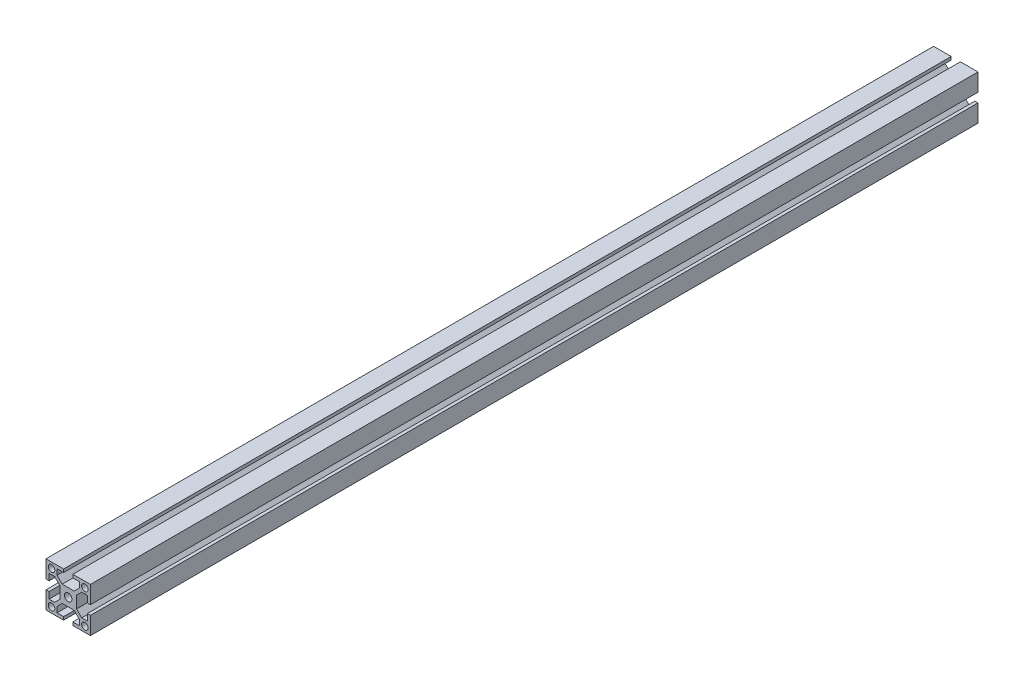
SolidWorks part; units mm, degrees
ref_plane "前视基准面" through (0, 0, 0) normal (0, 0, 1) x (1, 0, 0)
ref_plane "上视基准面" through (0, 0, 0) normal (0, 1, 0) x (1, 0, 0)
ref_plane "右视基准面" through (0, 0, 0) normal (1, 0, 0) x (0, 0, -1)
sketch "草图1" plane through (0, 0, 0) normal (0, 0, 1) x (1, 0, 0)
  line L0 (-0.0108, -0.0108) -> (37.1473, 37.1473) construction
  line L1 (-5.3895, -7.5108) -> (5.3678, -7.5108)
  line L2 (-7.5108, -5.3895) -> (-7.5108, 5.3678)
  line L3 (-5.3895, 7.4892) -> (5.3678, 7.4892)
  line L4 (7.4892, -5.3895) -> (7.4892, 5.3678)
  line L5 (-7.5108, -7.5108) -> (7.4892, 7.4892) construction
  line L6 (-7.5108, 7.4892) -> (7.4892, -7.5108) construction
  line L7 (7.4892, 5.3678) -> (12.1605, 10.0392)
  line L8 (19.9892, 19.9892) -> (19.9892, 4.1392)
  line L9 (19.9892, 19.9892) -> (4.1392, 19.9892)
  line L10 (19.9892, 4.1392) -> (17.1892, 4.1392)
  line L11 (4.1392, 19.9892) -> (4.1392, 17.1892)
  line L12 (17.1892, 4.1392) -> (17.1892, 10.0392)
  line L13 (12.1605, 10.0392) -> (17.1892, 10.0392)
  line L14 (4.1392, 17.1892) -> (10.0392, 17.1892)
  line L15 (10.0392, 12.1605) -> (10.0392, 17.1892)
  line L16 (5.3678, 7.4892) -> (10.0392, 12.1605)
  line L17 (-5.3895, 7.4892) -> (-10.0608, 12.1605)
  line L18 (-10.0608, 12.1605) -> (-10.0608, 17.1892)
  line L19 (-4.1608, 17.1892) -> (-10.0608, 17.1892)
  line L20 (-12.1822, 10.0392) -> (-17.2108, 10.0392)
  line L21 (-17.2108, 4.1392) -> (-17.2108, 10.0392)
  line L22 (-4.1608, 19.9892) -> (-4.1608, 17.1892)
  line L23 (-20.0108, 4.1392) -> (-17.2108, 4.1392)
  line L24 (-20.0108, 19.9892) -> (-4.1608, 19.9892)
  line L25 (-20.0108, 19.9892) -> (-20.0108, 4.1392)
  line L26 (-7.5108, 5.3678) -> (-12.1822, 10.0392)
  line L27 (-7.5108, -5.3895) -> (-12.1822, -10.0608)
  line L28 (-20.0108, -20.0108) -> (-20.0108, -4.1608)
  line L29 (-20.0108, -20.0108) -> (-4.1608, -20.0108)
  line L30 (-20.0108, -4.1608) -> (-17.2108, -4.1608)
  line L31 (-4.1608, -20.0108) -> (-4.1608, -17.2108)
  line L32 (-17.2108, -4.1608) -> (-17.2108, -10.0608)
  line L33 (-12.1822, -10.0608) -> (-17.2108, -10.0608)
  line L34 (-4.1608, -17.2108) -> (-10.0608, -17.2108)
  line L35 (-10.0608, -12.1822) -> (-10.0608, -17.2108)
  line L36 (-5.3895, -7.5108) -> (-10.0608, -12.1822)
  line L37 (5.3678, -7.5108) -> (10.0392, -12.1822)
  line L38 (10.0392, -12.1822) -> (10.0392, -17.2108)
  line L39 (4.1392, -17.2108) -> (10.0392, -17.2108)
  line L40 (12.1605, -10.0608) -> (17.1892, -10.0608)
  line L41 (17.1892, -4.1608) -> (17.1892, -10.0608)
  line L42 (4.1392, -20.0108) -> (4.1392, -17.2108)
  line L43 (19.9892, -4.1608) -> (17.1892, -4.1608)
  line L44 (19.9892, -20.0108) -> (4.1392, -20.0108)
  line L45 (19.9892, -20.0108) -> (19.9892, -4.1608)
  line L46 (7.4892, -5.3895) -> (12.1605, -10.0608)
  circle A0 centre (-0.0108, -0.0108) radius 3.4
  circle A1 centre (15.0142, 15.0142) radius 2.95
  circle A2 centre (-15.0358, 15.0142) radius 2.95
  circle A3 centre (-15.0358, -15.0358) radius 2.95
  circle A4 centre (15.0142, -15.0358) radius 2.95
  point P59 (0, 0)
  point P61 (0, 0)
  dimension "D1" = 6.8
  dimension "D4" = 5.9
  dimension "D2" = 15
  dimension "D3" = 15
  dimension "D5" = 2.8
  dimension "D6" = 7.5
  dimension "D7" = 3
  dimension "D8" = 0.0153
extrude "凸台-拉伸1" add sketch "草图1" along normal blind 800
